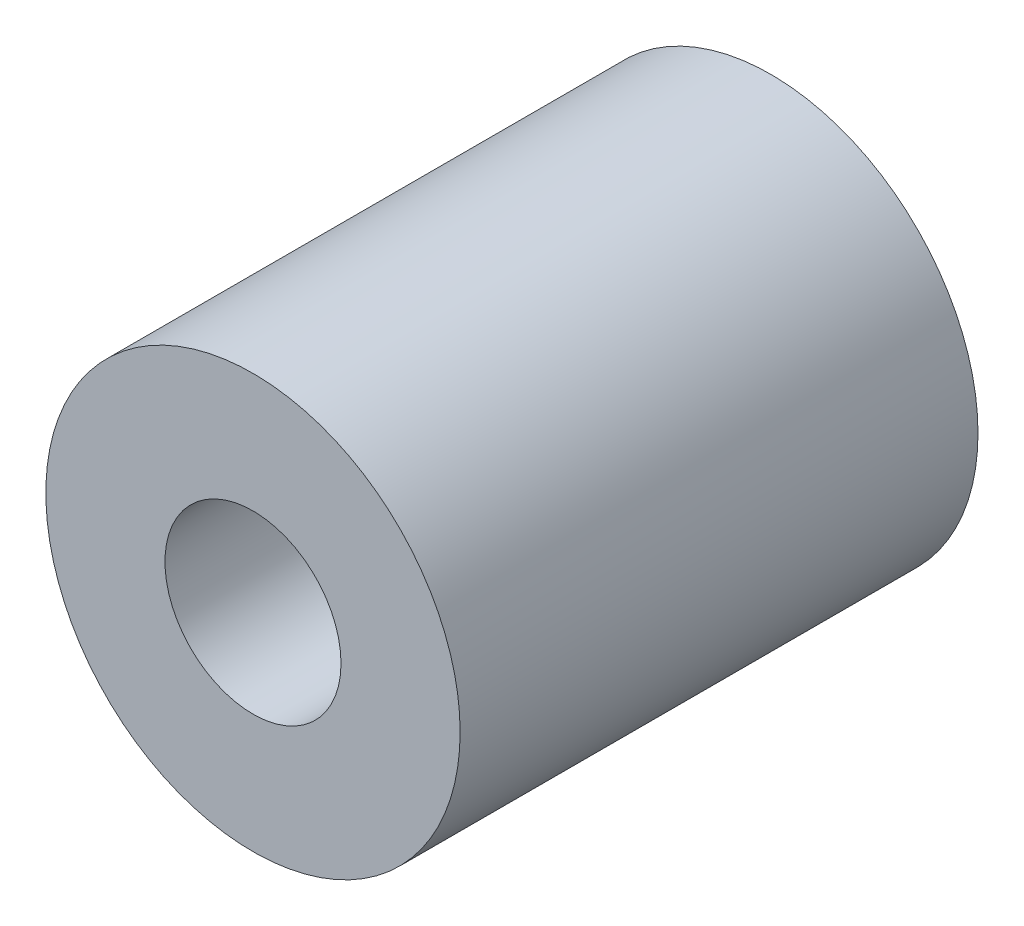
SolidWorks part; units mm, degrees
ref_plane "前视基准面" through (0, 0, 0) normal (0, 0, 1) x (1, 0, 0)
ref_plane "上视基准面" through (0, 0, 0) normal (0, 1, 0) x (1, 0, 0)
ref_plane "右视基准面" through (0, 0, 0) normal (1, 0, 0) x (0, 0, -1)
sketch "草图1" plane through (0, 0, 0) normal (0, 0, 1) x (1, 0, 0)
  circle A0 centre (0, 0) radius 4
  circle A1 centre (0, 0) radius 1.7
  point P3 (0, 0)
  dimension "D1" = 3.4
  dimension "D2" = 8
extrude "凸台-拉伸1" add sketch "草图1" along normal blind 10
